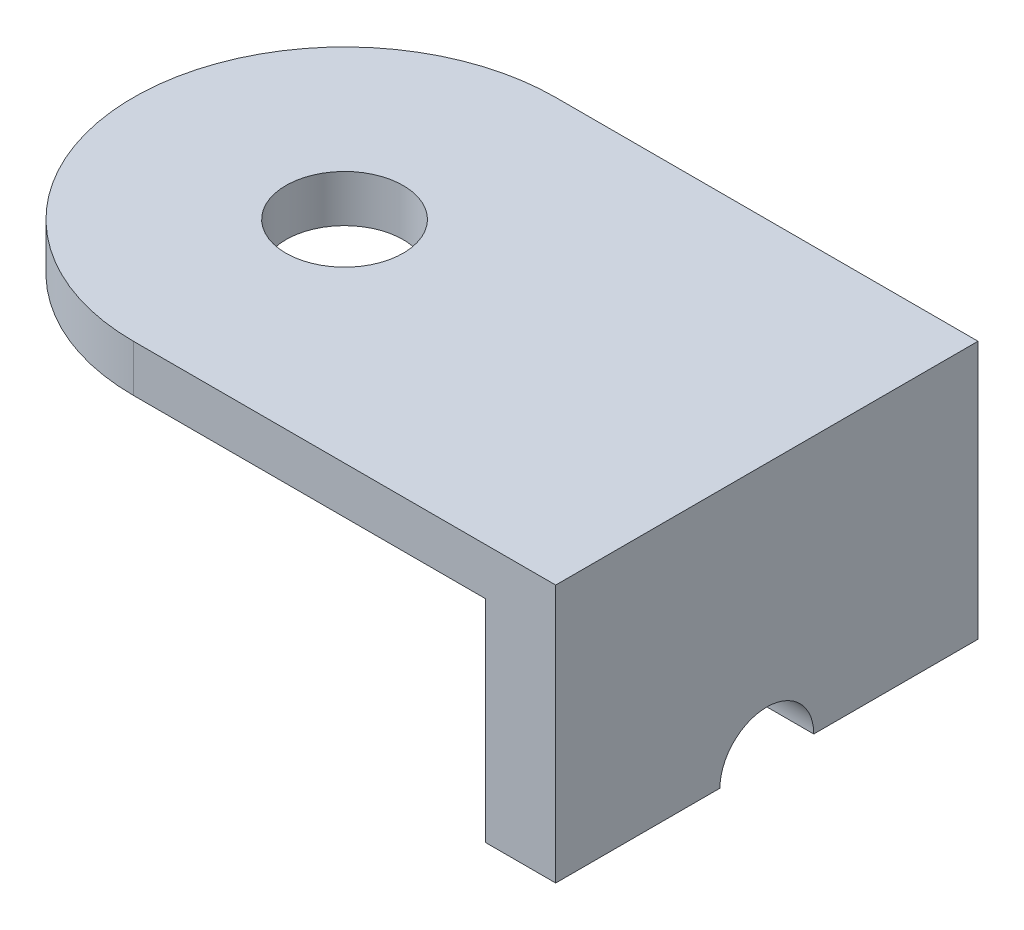
SolidWorks part; units mm, degrees
ref_plane "Front Plane" through (0, 0, 0) normal (0, 0, 1) x (1, 0, 0)
ref_plane "Top Plane" through (0, 0, 0) normal (0, 1, 0) x (1, 0, 0)
ref_plane "Right Plane" through (0, 0, 0) normal (1, 0, 0) x (0, 0, -1)
sketch "Sketch1" plane through (0, 0, 0) normal (0, 1, 0) x (1, 0, 0)
  line L1 (0, 9) -> (18, 9)
  line L2 (0, -9) -> (18, -9)
  line L3 (18, 9) -> (18, -9)
  circle A0 centre (0, 0) radius 2.5
  arc A1 (0, 9) -> (0, -9) centre (0, 0) ccw
  dimension "D1" = 5
  dimension "D2" = 18
extrude "Boss-Extrude1" add sketch "Sketch1" along normal blind 2
sketch "Sketch2" plane through (18, 0, 0) normal (1, 0, 0) x (0, 0, -1)
  line L0 (9, 0) -> (-9, 0)
  line L1 (9, 0) -> (9, -9)
  line L2 (-9, 0) -> (-9, -9)
  line L3 (9, -9) -> (2, -9)
  line L4 (-2, -9) -> (-9, -9)
  arc A0 (2, -9) -> (-2, -9) centre (0, -9) ccw
extrude "Boss-Extrude2" add sketch "Sketch2" against normal blind 3
